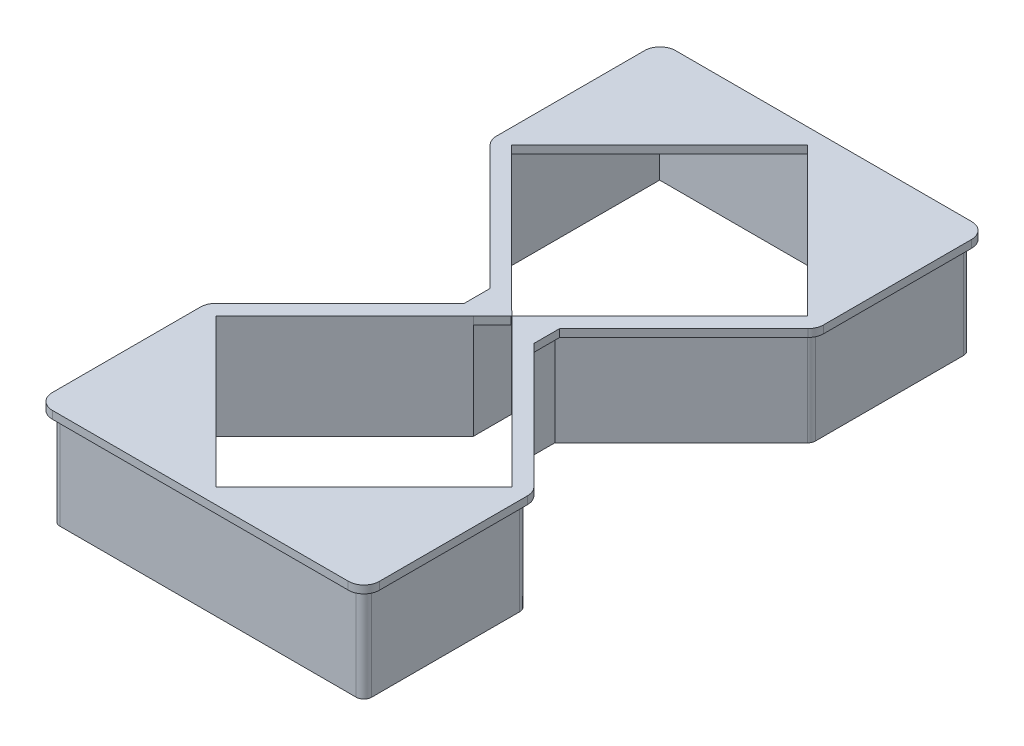
SolidWorks part; units mm, degrees
ref_plane "前视基准面" through (0, 0, 0) normal (0, 0, 1) x (1, 0, 0)
ref_plane "上视基准面" through (0, 0, 0) normal (0, 1, 0) x (1, 0, 0)
ref_plane "右视基准面" through (0, 0, 0) normal (1, 0, 0) x (0, 0, -1)
other "Configuration Table"
sketch "草图1" plane through (0, 0, 0) normal (0, 1, 0) x (1, 0, 0)
  line L18 (-2.3993, 68.9999) -> (-2.3993, 91.9999)
  line L22 (17.6005, 43.9942) -> (17.6005, 48.006)
  line L23 (46.0007, 94.3999) -> (0.0007, 94.3999)
  line L26 (48.4007, 68.9999) -> (48.4007, 91.9999)
  line L29 (28.4009, 43.9942) -> (28.4009, 48.006)
  line L32 (-1.6963, 67.3028) -> (17.6005, 48.006)
  line L36 (47.6978, 67.3028) -> (28.4009, 48.006)
  line L38 (-2.3993, 23.0003) -> (-2.3993, 0.0003)
  line L40 (48.4007, 23.0003) -> (48.4007, 0.0003)
  line L45 (0.0007, -2.3993) -> (45.9542, -2.3993)
  line L51 (-1.6963, 24.6973) -> (17.6005, 43.9942)
  line L53 (28.4009, 43.9942) -> (47.6978, 24.6973)
  arc A0 (0.0007, 94.3999) -> (-2.3993, 91.9999) centre (0.0007, 91.9999) ccw
  arc A1 (46.0007, 94.3999) -> (48.4007, 91.9999) centre (46.0007, 91.9999) cw
  arc A2 (-2.3993, 68.9999) -> (-1.6963, 67.3028) centre (0.0007, 68.9999) ccw
  arc A3 (48.4007, 68.9999) -> (47.6978, 67.3028) centre (46.0007, 68.9999) cw
  arc A4 (-1.6963, 24.6973) -> (-2.3993, 23.0003) centre (0.0007, 23.0003) ccw
  arc A5 (-2.3993, 0.0003) -> (0.0007, -2.3993) centre (0, 0) ccw
  arc A6 (45.9542, -2.3993) -> (48.4007, 0.0003) centre (46.0007, 0.0003) ccw
  arc A7 (47.6978, 24.6973) -> (48.4007, 23.0003) centre (46.0007, 23.0003) cw
extrude "凸台-拉伸2" add sketch "草图1" along normal blind 1.2 contours L29 L36 A3 L26 A1 L23 A0 L18 A2 L32 L22 L51 A4 L38 A5 L45 A6 L40 A7 L53
sketch "草图3" plane through (0, 0, 0) normal (0, -1, 0) x (1, 0, 0)
  line L0 (0, -23) -> (19.9998, -42.9998)
  line L1 (0, 0) -> (46, 0)
  line L2 (0, 0) -> (0, -23)
  line L4 (46, 0) -> (46, -23)
  line L5 (19.9998, -42.9998) -> (19.9998, -48.9389)
  line L6 (46, -23) -> (26.0002, -42.9998)
  line L7 (26.0002, -42.9998) -> (26.0002, -48.9998)
  line L8 (19.9998, -48.9389) -> (0, -68.9387)
  line L9 (26.0002, -48.9998) -> (46, -68.9387)
  line L11 (0, -68.9387) -> (0, -91.9387)
  line L12 (0, -91.9387) -> (46, -91.9387)
  line L13 (46, -68.9387) -> (46, -91.9387)
  line L14 (0, -93.1387) -> (46, -93.1387)
  line L15 (-1.2, -68.9387) -> (-1.2, -91.9387)
  line L16 (47.2, -68.9387) -> (47.2, -91.9387)
  line L17 (-1.2, 0) -> (-1.2, -23)
  line L18 (47.2, 0) -> (47.2, -23)
  line L19 (0, 1.2) -> (46, 1.2)
  line L21 (46.8485, -23.8485) -> (27.2002, -43.4969)
  line L23 (-0.8485, -23.8485) -> (18.7998, -43.4969)
  line L26 (-0.8485, -68.0902) -> (18.7998, -48.4419)
  line L29 (27.2002, -48.4419) -> (46.8485, -68.0902)
  line L33 (18.7998, -43.4969) -> (18.7998, -48.4419)
  line L35 (27.2002, -43.4969) -> (27.2002, -48.4419)
  arc A0 (-1.2, -91.9387) -> (0, -93.1387) centre (0, -91.9387) ccw
  arc A1 (-0.8485, -68.0902) -> (-1.2, -68.9387) centre (0, -68.9387) ccw
  arc A2 (46, -93.1387) -> (47.2, -91.9387) centre (46, -91.9387) ccw
  arc A3 (47.2, -68.9387) -> (46.8485, -68.0902) centre (46, -68.9387) ccw
  arc A4 (0, 1.2) -> (-1.2, 0) centre (0, 0) ccw
  arc A6 (46.8485, -23.8485) -> (47.2, -23) centre (46, -23) ccw
  arc A7 (47.2, 0) -> (46, 1.2) centre (46, 0) ccw
  arc A8 (-1.2, -23) -> (-0.8485, -23.8485) centre (0, -23) ccw
  point P13 (0, 0)
  point P15 (0, 0)
  point P23 (0, 0)
  point P24 (0, 0)
  point P30 (0, 0)
  point P38 (0, 0)
extrude "凸台-拉伸4" add sketch "草图3" along normal blind 15 contours L1 L4 L6 L7 L9 L13 L12 L11 L8 L5 L0 L2 | L19 A7 L18 A6 L21 L35 L29 A3 L16 A2 L14 A0 L15 A1 L26 L33 L23 A8 L17 A4
sketch "草图10" plane through (0, 0, 0) normal (0, -1, 0) x (1, 0, 0)
  line L10 (19.9998, -42.9998) -> (19.9998, -48.9389)
  line L21 (19.9998, -48.9389) -> (26.0002, -48.9998)
  line L22 (26.0002, -48.9998) -> (26.0002, -42.9998)
  line L23 (26.0002, -42.9998) -> (19.9998, -42.9998)
  line L24 (0, -68.9387) -> (23, -91.9387)
  line L25 (0, -91.9387) -> (46, -91.9387) construction
  line L26 (23, -91.9387) -> (46, -68.9387)
  line L27 (46, -68.9387) -> (26.0002, -48.9998)
  line L28 (19.9998, -48.9389) -> (0, -68.9387)
  line L29 (23, -45.9694) -> (19.9998, -48.9389)
  line L30 (26.0002, -48.9998) -> (23, -45.9694)
  point P8 (23, -45.9694)
sketch "草图11" plane through (0, 0, 0) normal (0, -1, 0) x (-1, 0, 0)
  line L0 (0, 23) -> (-23, 0)
  line L1 (0, 0) -> (-46, 0) construction
  line L2 (-23, 0) -> (-46, 23)
  line L3 (-46, 23) -> (-26.0002, 42.9998)
  line L5 (-19.9998, 42.9998) -> (0, 23)
  line L6 (-23, 45.9694) -> (-26.0002, 42.9998)
  line L7 (-19.9998, 42.9998) -> (-23, 45.9694)
  line L8 (-19.9998, 48.9389) -> (-23, 45.9694)
  line L9 (-26.0002, 48.9998) -> (-23, 45.9694)
  line M9 (0, 23) -> (-19.9998, 42.9998)
  line M17 (-26.0002, 42.9998) -> (-46, 23)
extrude "切除-拉伸13" cut sketch "草图11" against normal up to next contours L7 L6 L2 L0 M9 M17
sketch "草图16" plane through (0, 0, 0) normal (0, -1, 0) x (1, 0, 0)
  line L0 (0, -68.9387) -> (23, -91.9387)
  line L1 (0, -91.9387) -> (46, -91.9387) construction
  line L2 (23, -91.9387) -> (46, -68.9387)
  line L3 (46, -68.9387) -> (26.0002, -48.9998)
  line L4 (26.0002, -48.9998) -> (23.0711, -46.0412)
  line L5 (22.9289, -46.0397) -> (19.9998, -48.9389)
  line L6 (19.9998, -48.9389) -> (0, -68.9387)
  line L8 (23, -45.9694) -> (26.0002, -42.9998) construction
  line L10 (19.9998, -42.9998) -> (23, -45.9694) construction
  line L11 (22.9289, -45.899) -> (23.0711, -45.899)
  line L12 (22.9289, -45.899) -> (22.9289, -46.0397)
  line L13 (23.0711, -45.899) -> (23.0711, -46.0412)
extrude "切除-拉伸15" cut sketch "草图16" against normal up to next
sketch "草图17" plane through (0, 0, 0) normal (1, 0, 0) x (0, 0, -1)
  line L1 (10, -15) -> (15, -15)
  line L5 (15, -15) -> (20, -15)
  line L7 (15, -11) -> (20, -11)
  line L8 (20, -15) -> (20, -11)
  line L9 (20, -11) -> (10, -11)
  line L10 (20, -11) -> (20, -15)
  line L11 (20, -15) -> (10, -15)
  line L12 (10, -11) -> (10, -15)
  line M3 (0, -15) -> (23, -15)
extrude "切除-拉伸16" cut sketch "草图17" against normal up to next contours L9 L12 L8 L7 M3
sketch "草图18" plane through (35.3485, 0, -35.3485) normal (0.7071, 0, -0.7071) x (-0.7071, 0, -0.7071)
  line L0 (-16.2635, -15) -> (11.5235, -15) construction
  line L2 (-2.37, -15) -> (5.13, -15)
  line L3 (-2.37, -15) -> (-9.87, -15)
  line L4 (-9.87, -15) -> (-9.87, -5)
  line L5 (-9.87, -5) -> (5.13, -5)
  line L6 (5.13, -5) -> (5.13, -15)
  point P0 (-2.37, -15)
extrude "切除-拉伸17" cut sketch "草图18" against normal up to next
